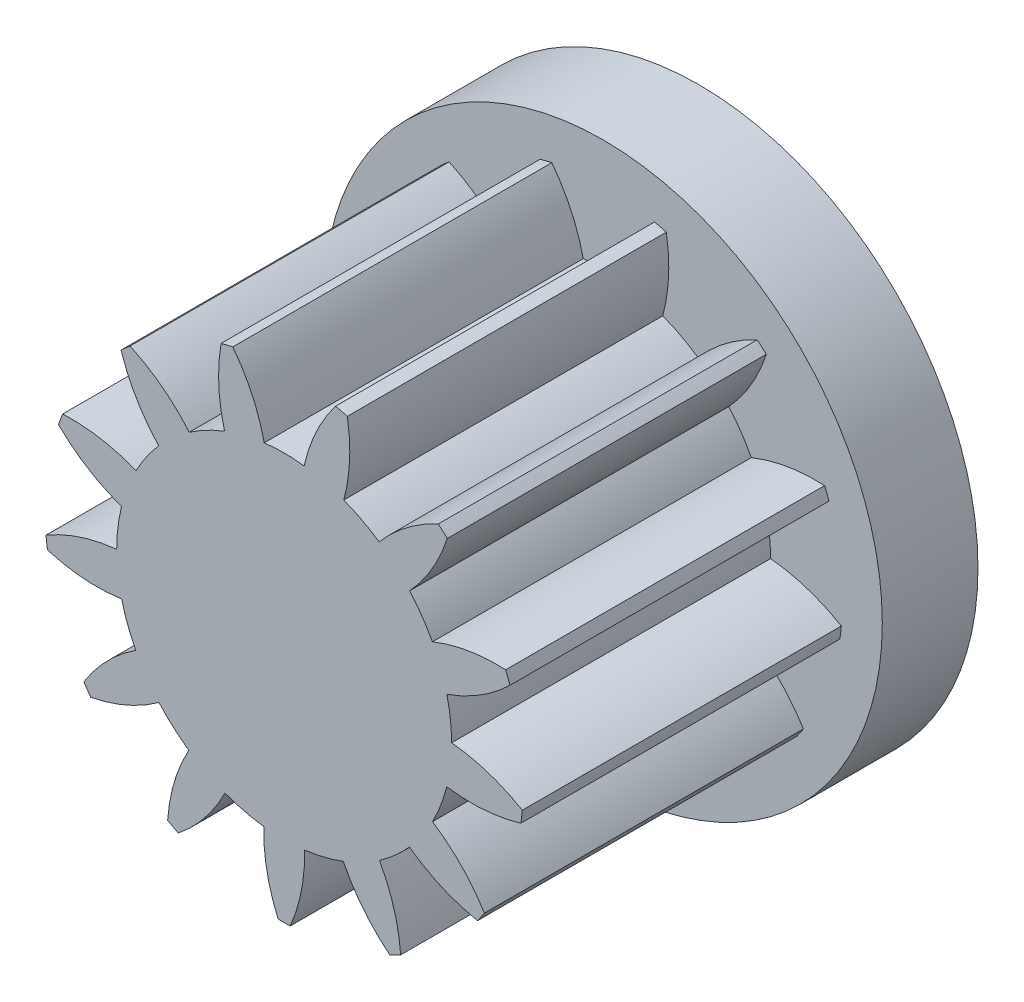
SolidWorks part; units mm, degrees
ref_plane "Front Plane" through (0, 0, 0) normal (0, 0, 1) x (1, 0, 0)
ref_plane "Top Plane" through (0, 0, 0) normal (0, 1, 0) x (1, 0, 0)
ref_plane "Right Plane" through (0, 0, 0) normal (1, 0, 0) x (0, 0, -1)
sketch "Sketch1" plane through (0, 0, 0) normal (0, 0, 1) x (1, 0, 0)
  circle A0 centre (0, 0) radius 8.75
  dimension "D1" = 17.5
extrude "Boss-Extrude1" add sketch "Sketch1" along normal blind 3
sketch "Sketch2" plane through (0, 0, 3) normal (0, 0, 1) x (1, 0, 0)
  line L0 (0, 13.3499) -> (0, -11.1917) construction
  line L1 (-11.7926, 0) -> (-5.25, 0) construction
  line L2 (0, 0) -> (2.575, 10.4442) construction
  line L3 (0, 0) -> (1.8688, 4.9061) construction
  line L4 (0, 0) -> (3.9347, 3.4757) construction
  line L5 (0, 0) -> (10.798, 0) construction
  arc A0 (2.9767, 4.3246) -> (1.8688, 4.9061) centre (0, 0) ccw
  arc A1 (-6.9428, 2.8368) -> (-7.0776, 2.4815) centre (0, 0) ccw
  arc A2 (1.6103, 7.3251) -> (0.626, 5.2125) centre (5.8976, 4.0419) ccw
  arc A3 (1.9793, 7.2341) -> (1.8688, 4.9061) centre (-3.3428, 6.3201) cw
  arc A4 (4.83, 5.7377) -> (2.9767, 4.3246) centre (7.1004, 0.8382) ccw
  arc A5 (5.1144, 5.4857) -> (3.9347, 3.4757) centre (-0.0228, 7.1497) cw
  arc A6 (6.9432, 2.8359) -> (4.6454, 2.4459) centre (6.6766, -2.5575) ccw
  arc A7 (7.0779, 2.4806) -> (5.0993, 1.249) centre (3.3024, 6.3413) cw
  arc A8 (7.4658, -0.7156) -> (5.25, 0.0069) centre (4.7233, -5.3674) ccw
  arc A9 (7.42, -1.0928) -> (5.0956, -1.2638) centre (5.8711, 4.0803) cw
  arc A10 (6.2781, -4.1032) -> (4.6518, -2.4337) centre (1.6879, -6.9476) ccw
  arc A11 (6.0622, -4.4159) -> (3.9246, -3.4871) centre (7.0948, 0.8845) cw
  arc A12 (3.6521, -6.5507) -> (2.988, -4.3168) centre (-1.7341, -6.9362) ccw
  arc A13 (3.3156, -6.7273) -> (1.8546, -4.9115) centre (6.6931, -2.514) cw
  arc A14 (0.1895, -7.4976) -> (0.6397, -5.2109) centre (-4.7589, -5.3358) ccw
  arc A15 (-0.1905, -7.4976) -> (-0.6403, -5.2108) centre (4.7582, -5.3365) cw
  arc A16 (-3.3165, -6.7269) -> (-1.8552, -4.9113) centre (-6.6935, -2.5131) ccw
  arc A17 (-3.653, -6.5502) -> (-2.9886, -4.3164) centre (1.7332, -6.9364) cw
  arc A18 (-6.0628, -4.4151) -> (-3.9251, -3.4865) centre (-7.0947, 0.8854) ccw
  arc A19 (-6.2786, -4.1023) -> (-4.6522, -2.4331) centre (-1.6889, -6.9474) cw
  arc A20 (-7.4201, -1.0919) -> (-5.0958, -1.2631) centre (-5.8705, 4.081) ccw
  arc A21 (-7.4659, -0.7146) -> (-5.25, 0.0076) centre (-4.724, -5.3667) cw
  arc A22 (-7.0776, 2.4815) -> (-5.0991, 1.2497) centre (-3.3015, 6.3418) ccw
  arc A23 (-6.9428, 2.8368) -> (-4.6451, 2.4465) centre (-6.677, -2.5566) cw
  arc A24 (-5.1137, 5.4864) -> (-3.9342, 3.4762) centre (0.0238, 7.1497) ccw
  arc A25 (-4.8292, 5.7383) -> (-2.9761, 4.325) centre (-7.1003, 0.8391) cw
  arc A26 (-1.9783, 7.2344) -> (-1.8681, 4.9064) centre (3.3437, 6.3196) ccw
  arc A27 (-1.6093, 7.3253) -> (-0.6253, 5.2126) centre (-5.897, 4.0427) cw
  arc A28 (-7.4659, -0.7146) -> (-7.4201, -1.0919) centre (0, 0) ccw
  arc A29 (-6.2786, -4.1023) -> (-6.0628, -4.4151) centre (0, 0) ccw
  arc A30 (-3.653, -6.5502) -> (-3.3165, -6.7269) centre (0, 0) ccw
  arc A31 (-0.1905, -7.4976) -> (0.1895, -7.4976) centre (0, 0) ccw
  arc A32 (3.3156, -6.7273) -> (3.6521, -6.5507) centre (0, 0) ccw
  arc A33 (6.0622, -4.4159) -> (6.2781, -4.1032) centre (0, 0) ccw
  arc A34 (7.42, -1.0928) -> (7.4658, -0.7156) centre (0, 0) ccw
  arc A35 (7.0779, 2.4806) -> (6.9432, 2.8359) centre (0, 0) ccw
  arc A36 (5.1144, 5.4857) -> (4.83, 5.7377) centre (0, 0) ccw
  arc A37 (1.9793, 7.2341) -> (1.6103, 7.3251) centre (0, 0) ccw
  arc A38 (-1.6093, 7.3253) -> (-1.9783, 7.2344) centre (0, 0) ccw
  arc A39 (-4.8292, 5.7383) -> (-5.1137, 5.4864) centre (0, 0) ccw
  arc A40 (0.626, 5.2125) -> (-0.6253, 5.2126) centre (0, 0) ccw
  arc A41 (-1.8681, 4.9064) -> (-2.9761, 4.325) centre (0, 0) ccw
  arc A42 (-3.9342, 3.4762) -> (-4.6451, 2.4465) centre (0, 0) ccw
  arc A43 (-5.0991, 1.2497) -> (-5.25, 0.0076) centre (0, 0) ccw
  arc A44 (-5.0958, -1.2631) -> (-4.6522, -2.4331) centre (0, 0) ccw
  arc A45 (-3.9251, -3.4865) -> (-2.9886, -4.3164) centre (0, 0) ccw
  arc A46 (-1.8552, -4.9113) -> (-0.6403, -5.2108) centre (0, 0) ccw
  arc A47 (0.6397, -5.2109) -> (1.8546, -4.9115) centre (0, 0) ccw
  arc A48 (2.988, -4.3168) -> (3.9246, -3.4871) centre (0, 0) ccw
  arc A49 (4.6518, -2.4337) -> (5.0956, -1.2638) centre (0, 0) ccw
  arc A50 (5.25, 0) -> (5.0993, 1.249) centre (0, 0) ccw
  arc A51 (4.6454, 2.4459) -> (3.9347, 3.4757) centre (0, 0) ccw
  dimension "D1" = 10.5
  dimension "D2" = 15
  dimension "D3" = 13.85
  dimension "D6" = 5.4
  dimension "D4" = 0.38
  dimension "D5" = 1.28
  dimension "D7" = 13
  dimension "D8" = 27.692
extrude "Boss-Extrude2" add sketch "Sketch2" along normal blind 10
scale "Scale1" scale about centroid uniform scaling yes scale factor 1.9
